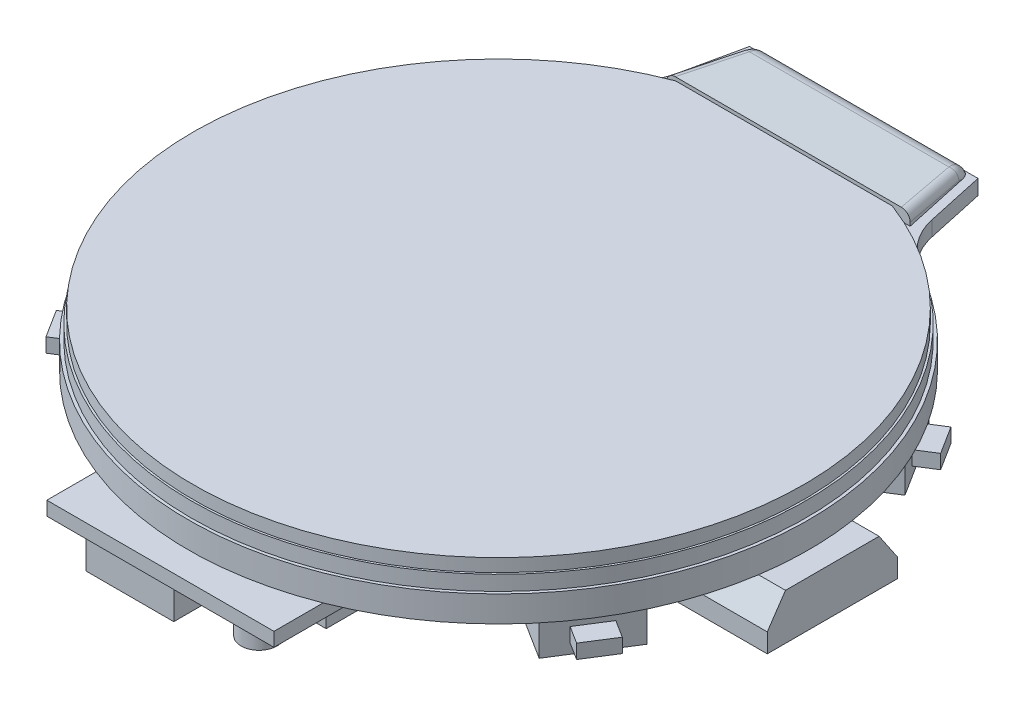
SolidWorks part; units mm, degrees
ref_plane "Front Plane" through (0, 0, 0) normal (0, 0, 1) x (1, 0, 0)
ref_plane "Top Plane" through (0, 0, 0) normal (0, 1, 0) x (1, 0, 0)
ref_plane "Right Plane" through (0, 0, 0) normal (1, 0, 0) x (0, 0, -1)
sketch "Sketch1" plane through (0, 0, 0) normal (0, 1, 0) x (1, 0, 0)
  line L0 (-6.25, 16.4689) -> (6.25, 16.4689)
  line L1 (0, -55) -> (0, 55) construction
  arc A0 (-6.25, 16.4689) -> (6.25, 16.4689) centre (0, 0) ccw
  point P5 (0, 16.4689)
  dimension "D1" = 35.23
  dimension "D2" = 12.5
extrude "Boss-Extrude1" add sketch "Sketch1" along normal blind 0.75 contours A0 L0
sketch "Sketch2" plane through (0, 0, 0) normal (0, 1, 0) x (1, 0, 0)
  line L0 (6.59, 21.07) -> (-6.59, 21.07)
  line L1 (0, -0.4125) -> (0, 0.4125) construction
  line L2 (6.59, 21.07) -> (7.33, 17.6702)
  line L3 (-6.59, 21.07) -> (-7.33, 17.6702)
  arc A0 (-9.09, 15.2225) -> (9.09, 15.2225) centre (0, 0) ccw
  arc A1 (7.33, 17.6702) -> (9.09, 15.2225) centre (11.0329, 18.4761) ccw
  arc A2 (-7.33, 17.6702) -> (-9.09, 15.2225) centre (-11.0329, 18.4761) cw
  point P5 (0, -17.73)
  point P6 (0, 21.07)
  dimension "D1" = 35.46
  dimension "D2" = 38.8
  dimension "D3" = 13.18
  dimension "D4" = 18.18
  dimension "D5" = 14.66
extrude "Boss-Extrude2" add sketch "Sketch2" against normal blind 0.86 contours L3 A2 A0 A1 L2 L0
sketch "Sketch3" plane through (0, -0.86, 0) normal (0, -1, 0) x (1, 0, 0)
  circle A0 centre (0, 0) radius 17.905
  dimension "D1" = 35.81
extrude "Boss-Extrude3" add sketch "Sketch3" along normal blind 1.5
sketch "Sketch4" plane through (0, -2.36, 0) normal (0, -1, 0) x (1, 0, 0)
  line L0 (0, -1.7105) -> (0, 1.7105) construction
  line L1 (6.55, 0.46) -> (-6.55, 0.46)
  line L2 (6.55, 0.46) -> (6.55, 19.5)
  line L3 (6.55, 19.5) -> (-6.55, 19.5)
  line L4 (-6.55, 0.46) -> (-6.55, 19.5)
  line L5 (6.55, 0.46) -> (-6.55, 19.5) construction
  line L6 (6.55, 19.5) -> (-6.55, 0.46) construction
  line L7 (6.59, -21.07) -> (-6.59, -21.07) construction
  point P0 (0, 9.98)
  dimension "D1" = 13.1
  dimension "D2" = 19.04
  dimension "D3" = 40.57
extrude "Boss-Extrude4" add sketch "Sketch4" along normal blind 0.8
sketch "Sketch5" plane through (0, -3.16, 0) normal (0, -1, 0) x (1, 0, 0)
  line L0 (0, -2.1505) -> (0, 2.1505) construction
  line L1 (5.165, 1.845) -> (-5.165, 1.845)
  line L2 (5.165, 1.845) -> (5.165, 15.105)
  line L3 (5.165, 15.105) -> (-5.165, 15.105)
  line L4 (-5.165, 1.845) -> (-5.165, 15.105)
  line L5 (5.165, 1.845) -> (-5.165, 15.105) construction
  line L6 (5.165, 15.105) -> (-5.165, 1.845) construction
  line L7 (0, 1.845) -> (0, 0.46) construction
  line L8 (5.165, 1.845) -> (6.55, 1.845) construction
  line L9 (6.55, 0.46) -> (6.55, 19.5) construction
  line L10 (-6.55, 0.46) -> (6.55, 0.46) construction
  point P0 (0, 8.475)
  dimension "D1" = 10.33
  dimension "D2" = 13.26
extrude "Boss-Extrude5" add sketch "Sketch5" along normal blind 1.96
sketch "Sketch6" plane through (0, -3.16, 0) normal (0, -1, 0) x (1, 0, 0)
  line L0 (-6.55, 19.5) -> (-6.55, 0.46) construction
  line L1 (-4.6, 19.2) -> (0.47, 19.2)
  line L2 (-4.6, 19.2) -> (-4.6, 17.12)
  line L3 (-4.6, 17.12) -> (0.47, 17.12)
  line L4 (0.47, 19.2) -> (0.47, 17.12)
  line L5 (-4.6, 19.2) -> (0.47, 17.12) construction
  line L6 (-4.6, 17.12) -> (0.47, 19.2) construction
  line L7 (6.55, 19.5) -> (-6.55, 19.5) construction
  point P0 (-2.065, 18.16)
  dimension "D1" = 1.95
  dimension "D2" = 5.07
  dimension "D3" = 2.08
  dimension "D4" = 0.3
extrude "Boss-Extrude6" add sketch "Sketch6" along normal blind 1.91
sketch "Sketch7" plane through (0, -3.16, 0) normal (0, -1, 0) x (1, 0, 0)
  line L0 (6.55, 0.46) -> (6.55, 19.5) construction
  line L1 (6.55, 19.5) -> (-6.55, 19.5) construction
  circle A0 centre (4.14, 17.95) radius 1.035
  dimension "D1" = 2.07
  dimension "D2" = 2.41
  dimension "D3" = 1.55
extrude "Boss-Extrude7" add sketch "Sketch7" along normal blind 1.4
sketch "Sketch8" plane through (0, -2.36, 0) normal (0, -1, 0) x (1, 0, 0)
  line L0 (16, -7.4455) -> (13.5968, -11.25)
  line L1 (16, -7.4455) -> (13.8864, -6.1103)
  line L2 (13.5968, -11.25) -> (11.4831, -9.9149)
  line L3 (13.8864, -6.1103) -> (11.4831, -9.9149)
  line L4 (16, -7.4455) -> (11.4831, -9.9149) construction
  line L5 (13.5968, -11.25) -> (13.8864, -6.1103) construction
  line L6 (-16, -7.4455) -> (-13.5968, -11.25)
  line L7 (-16, -7.4455) -> (-13.8864, -6.1103)
  line L8 (-13.5968, -11.25) -> (-11.4831, -9.9149)
  line L9 (-13.8864, -6.1103) -> (-11.4831, -9.9149)
  line L10 (-16, -7.4455) -> (-11.4831, -9.9149) construction
  line L11 (-13.5968, -11.25) -> (-13.8864, -6.1103) construction
  line L12 (-16, 7.4455) -> (-13.5968, 11.25)
  line L13 (-16, 7.4455) -> (-13.8864, 6.1103)
  line L14 (-13.5968, 11.25) -> (-11.4831, 9.9149)
  line L15 (-13.8864, 6.1103) -> (-11.4831, 9.9149)
  line L16 (-16, 7.4455) -> (-11.4831, 9.9149) construction
  line L17 (-13.5968, 11.25) -> (-13.8864, 6.1103) construction
  line L18 (13.8864, 6.1103) -> (11.4831, 9.9149)
  line L19 (13.8864, 6.1103) -> (16, 7.4455)
  line L20 (11.4831, 9.9149) -> (13.5968, 11.25)
  line L21 (16, 7.4455) -> (13.5968, 11.25)
  line L22 (13.8864, 6.1103) -> (13.5968, 11.25) construction
  line L23 (11.4831, 9.9149) -> (16, 7.4455) construction
  line L24 (13.7416, 8.6802) -> (-13.7416, -8.6802) construction
  line L25 (13.7416, -8.6802) -> (-13.7416, 8.6802) construction
  line L26 (13.7416, -8.6802) -> (13.7416, 8.6802) construction
  line L27 (3.2285, 0) -> (-3.2285, 0) construction
  point P1 (13.7416, -8.6802)
  point P2 (-13.7416, -8.6802)
  point P3 (-13.7416, 8.6802)
  point P8 (13.7416, 8.6802)
  point P18 (0, 0)
  point P26 (0, 0)
  point P27 (13.7416, 0)
  dimension "D1" = 4.5
  dimension "D2" = 2.5
  dimension "D3" = 22.5
  dimension "D4" = 32
extrude "Boss-Extrude8" add sketch "Sketch8" along normal blind 1.95
sketch "Sketch9" plane through (-14.7984, 0, -9.3477) normal (-0.8455, 0, -0.534) x (-0.534, 0, 0.8455)
  line L0 (2.25, -4.31) -> (-2.25, -4.31) construction
  line L1 (-0.955, -2.925) -> (0.955, -2.925)
  line L2 (-0.955, -2.925) -> (-0.955, -3.745)
  line L3 (-0.955, -3.745) -> (0.955, -3.745)
  line L4 (0.955, -2.925) -> (0.955, -3.745)
  line L5 (-0.955, -2.925) -> (0.955, -3.745) construction
  line L6 (-0.955, -3.745) -> (0.955, -2.925) construction
  line L7 (-2.25, -4.31) -> (-2.25, -2.36) construction
  point P0 (0, -3.335)
  point P8 (0, -4.31)
  point P9 (-0.955, -3.335)
  point P12 (-2.25, -3.335)
  dimension "D1" = 1.91
  dimension "D2" = 0.82
extrude "Boss-Extrude9" add sketch "Sketch9" along normal blind 1.2
mirror "Mirror1" about plane through (0, 0, 0) normal (0, 0, 1) of "Boss-Extrude9"
mirror "Mirror2" about plane through (0, 0, 0) normal (1, 0, 0) of "Mirror1", "Boss-Extrude9"
sketch "Sketch10" plane through (0, -2.36, 0) normal (0, -1, 0) x (-1, 0, 0)
  line L0 (-3.2285, 0) -> (3.2285, 0) construction
  line L1 (-19.255, 3.75) -> (-13.705, 3.75)
  line L2 (-19.255, 3.75) -> (-19.255, -3.75)
  line L3 (-19.255, -3.75) -> (-13.705, -3.75)
  line L4 (-13.705, 3.75) -> (-13.705, -3.75)
  line L5 (-19.255, 3.75) -> (-13.705, -3.75) construction
  line L6 (-19.255, -3.75) -> (-13.705, 3.75) construction
  arc A0 (6.55, -16.6639) -> (-6.55, -16.6639) centre (0, 0) ccw construction
  point P0 (-16.48, 0)
  point P9 (17.905, 0)
  dimension "D1" = 7.5
  dimension "D2" = 5.55
  dimension "D3" = 37.16
extrude "Boss-Extrude10" add sketch "Sketch10" along normal blind 2.65
sketch "Sketch11" plane through (19.255, 0, 0) normal (1, 0, 0) x (0, 0, -1)
  line L1 (3.75, -2.36) -> (-3.75, -2.36) construction
  line L2 (3.75, -2.36) -> (-3.75, -2.36) construction
  line L4 (3.75, -5.01) -> (3.75, -3.91)
  line L5 (3.75, -5.01) -> (3.75, -2.36) construction
  line L6 (2.7, -2.36) -> (3.75, -3.91)
  line L7 (3.75, -5.01) -> (-3.75, -5.01)
  line L8 (-3.75, -5.01) -> (-3.75, -3.91)
  line L9 (-3.75, -5.01) -> (-3.75, -2.36) construction
  line L10 (-2.7, -2.36) -> (-3.75, -3.91)
  line L11 (-16.6639, -2.36) -> (-3.75, -2.36) construction
  line L12 (4.3613, -9.2077) -> (-4.3613, -9.2077)
  line L13 (4.3613, -9.2077) -> (4.3613, -2.36)
  line L14 (4.3613, -2.36) -> (2.7, -2.36)
  line L15 (-4.3613, -9.2077) -> (-4.3613, -2.36)
  line L16 (4.3613, -9.2077) -> (-4.3613, -2.36) construction
  line L17 (4.3613, -2.36) -> (-4.3613, -9.2077) construction
  line L18 (-2.7, -2.36) -> (-4.3613, -2.36)
  point P6 (0, -5.7838)
  dimension "D1" = 5.4
  dimension "D2" = 1.1
extrude "Cut-Extrude1" cut sketch "Sketch11" against normal blind 3.65
sketch "Sketch12" plane through (0, 0, 0) normal (0, 1, 0) x (1, 0, 0)
  line L0 (-7.0253, 16.7189) -> (7.0253, 16.7189)
  line L1 (7.0253, 16.7189) -> (6.0783, 21.07)
  line L2 (6.59, 21.07) -> (-6.59, 21.07) construction
  line L3 (6.0783, 21.07) -> (-6.0783, 21.07)
  line L4 (-6.0783, 21.07) -> (-7.0253, 16.7189)
  line L5 (-6.59, 21.07) -> (-7.33, 17.6702) construction
  line L6 (6.59, 21.07) -> (7.33, 17.6702) construction
  line L7 (-6.25, 16.4689) -> (6.25, 16.4689) construction
  dimension "D1" = 0.5
  dimension "D2" = 0.5
  dimension "D3" = 0.25
extrude "Boss-Extrude11" add sketch "Sketch12" along normal blind 0.7
sketch "Sketch13" plane through (0, 0, 0) normal (1, 0, 0) x (0, 0, -1)
  line L0 (20.438, 0) -> (-20.438, 0) construction
  line L1 (21.07, 0.7) -> (21.07, 0) construction
  line L2 (16.7189, 0.7) -> (20.2259, 0.5764)
  line L3 (16.7189, 0.7) -> (16.7189, 1.6206)
  line L4 (16.7189, 1.6206) -> (21.6502, 1.0813)
  line L5 (21.6502, 1.0813) -> (21.07, 0)
  arc A0 (21.07, 0) -> (20.2259, 0.5764) centre (20.1922, -0.3793) ccw
extrude "Cut-Extrude2" cut sketch "Sketch13" against normal blind 10 and the other way blind 10
fillet "Fillet1" radius 0.5 4 edges at (6.152, 0.4104, -20.7314) (-6.152, 0.4104, -20.7314) (6.6437, 0.6382, -18.4724) (-6.6437, 0.6382, -18.4724)
sketch "Sketch14" plane through (0, 0, 0) normal (0, 1, 0) x (1, 0, 0)
  line L0 (15.8129, 9.9886) -> (-15.8129, -9.9886) construction
  line L1 (15.3029, 10.796) -> (16.323, 9.1812) construction
  line L2 (-15.3029, -10.796) -> (-16.323, -9.1812) construction
  line L3 (-15.8129, 9.9886) -> (15.8129, -9.9886) construction
  line L4 (-15.3029, 10.796) -> (-16.323, 9.1812) construction
  line L5 (15.3029, -10.796) -> (16.323, -9.1812) construction
